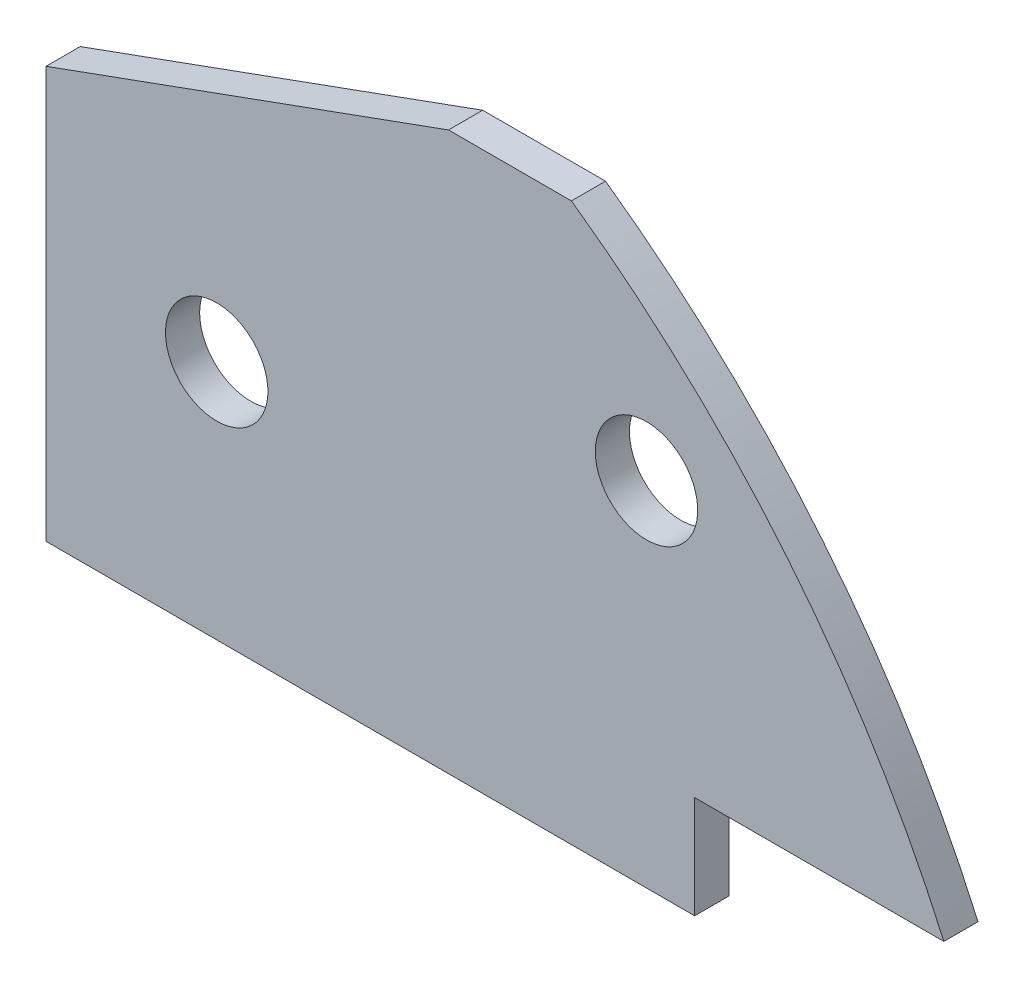
SolidWorks part; units mm, degrees
ref_plane "Front Plane" through (0, 0, 0) normal (0, 0, 1) x (1, 0, 0)
ref_plane "Top Plane" through (0, 0, 0) normal (0, 1, 0) x (1, 0, 0)
ref_plane "Right Plane" through (0, 0, 0) normal (1, 0, 0) x (0, 0, -1)
sketch "Sketch1" plane through (0, 0, 0) normal (0, 0, 1) x (1, 0, 0)
  line L2 (11, 25.5) -> (-11, 25.5)
  line L3 (-11, 25.5) -> (-22.79, 29.7803)
  line L4 (11, 25.5) -> (22.79, 29.7803)
  arc A0 (-22.79, 29.7803) -> (22.79, 29.7803) centre (0, 0) ccw
  arc A1 (-22.79, 29.7803) -> (22.79, 29.7803) centre (0, 0) ccw
  dimension "D2" = 37.5
extrude "Boss-Extrude1" add sketch "Sketch1" along normal blind 3 contours L3 A0 L4 L2
sketch "Sketch2" plane through (0, 0, 3) normal (0, 0, 1) x (1, 0, 0)
  line L0 (0, 0) -> (-25.8, 0) construction
  line L2 (0, 0) -> (0, 15.281) construction
  circle A4 centre (-25.4, 10.4969) radius 1.5
  circle A5 centre (-25.4, -10.4931) radius 1.5
  circle A6 centre (25.4, -10.4931) radius 1.5
  circle A7 centre (25.4, 10.4969) radius 1.5
  point P6 (-25.8, 0)
  dimension "D1" = 25.8
  dimension "D2" = 20.99
extrude "Cut-Extrude3" cut sketch "Sketch2" against normal blind 3
sketch "Sketch3" plane through (0, 0, 3) normal (0, 0, 1) x (1, 0, 0)
  line L1 (-30.76, 21.4493) -> (-30.76, -21.4493)
  line L3 (30.76, 21.4493) -> (30.76, -21.4493)
  arc A0 (-22.79, 29.7803) -> (22.79, 29.7803) centre (0, 0) ccw construction
  arc A1 (-30.76, 21.4493) -> (-30.76, -21.4493) centre (0, 0) ccw
  arc A2 (30.76, 21.4493) -> (30.76, -21.4493) centre (0, 0) cw
  point P10 (-30.76, 0)
extrude "Cut-Extrude4" cut sketch "Sketch3" against normal blind 10
sketch "Sketch4" plane through (0, 0, 3) normal (0, 0, 1) x (1, 0, 0)
  line L0 (-30.76, 21.4493) -> (-30.76, 16.4493) construction
  line L1 (-30.76, -21.4493) -> (-30.76, 21.4493) construction
  line L2 (30.76, 21.4493) -> (30.76, 16.4493) construction
  line L3 (30.76, 21.4493) -> (30.76, -21.4493) construction
  line L4 (-30.76, -21.4493) -> (-30.76, -16.4493) construction
  line L5 (30.76, -21.4493) -> (30.76, -16.4493) construction
  line L6 (-30.76, -16.4493) -> (-33.6997, -16.4493)
  line L7 (-30.76, 16.4493) -> (-33.6997, 16.4493)
  line L8 (30.76, 16.4493) -> (33.6997, 16.4493)
  line L9 (30.76, -16.4493) -> (33.6997, -16.4493)
  line L10 (30.76, -21.4493) -> (30.76, -16.4493)
  line L11 (30.76, 21.4493) -> (30.76, 16.4493)
  line L12 (-30.76, 16.4493) -> (-30.76, 21.4493)
  line L13 (-30.76, -21.4493) -> (-30.76, -16.4493)
  arc A0 (-33.6997, -16.4493) -> (33.6997, -16.4493) centre (0, 0) ccw
  arc A1 (-30.76, 21.4493) -> (-33.6997, 16.4493) centre (0, 0) ccw
  arc A2 (33.6997, 16.4493) -> (30.76, 21.4493) centre (0, 0) ccw
  line M2 (30.76, -21.4493) -> (30.76, 21.4493)
  line M8 (-30.76, 21.4493) -> (-30.76, -21.4493)
  dimension "D1" = 5
  dimension "D2" = 5
extrude "Boss-Extrude2" add sketch "Sketch4" against normal blind 3 contours L6 A0 M8 | A1 L7 M8 | L8 A2 M2 | A0 L9 M2
sketch "Sketch5" plane through (0, 0, 3) normal (0, 0, 1) x (1, 0, 0)
  line L0 (-30.76, 16.4493) -> (-30.2, 16.4493) construction
  line L1 (-30.76, -16.4493) -> (-30.2, -16.4493) construction
  line L2 (0, 0) -> (0, -3.3934) construction
  line L3 (-30.2, -16.4493) -> (-30.76, -16.4493)
  line L4 (-30.2, -16.4493) -> (-30.2, 16.4493)
  line L5 (-30.2, 16.4493) -> (-30.76, 16.4493)
  line L6 (-30.76, -16.4493) -> (-30.76, 16.4493)
  line L7 (30.76, -16.4493) -> (30.2, -16.4493) construction
  line L8 (30.76, 16.4493) -> (30.2, 16.4493) construction
  line L9 (30.76, -16.4493) -> (30.76, 16.4493)
  line L10 (30.2, 16.4493) -> (30.76, 16.4493)
  line L11 (30.2, -16.4493) -> (30.2, 16.4493)
  line L12 (30.2, -16.4493) -> (30.76, -16.4493)
  dimension "D2" = 0.56
extrude "Cut-Extrude5" cut sketch "Sketch5" against normal blind 3
sketch "Sketch6" plane through (0, 0, 3) normal (0, 0, 1) x (1, 0, 0)
  line L1 (-30.2, 16.4493) -> (-30, 16.4493)
  line L2 (-30.2, 16.4493) -> (-30.2, -16.4493)
  line L3 (-30.2, -16.4493) -> (-30, -16.4493)
  line L4 (-30, 16.4493) -> (-30, -16.4493)
  line L5 (30, 16.4493) -> (30, -16.4493)
  line L6 (30.2, -16.4493) -> (30, -16.4493)
  line L7 (30.2, 16.4493) -> (30.2, -16.4493)
  line L8 (30.2, 16.4493) -> (30, 16.4493)
  dimension "D1" = 0.2
extrude "Cut-Extrude6" cut sketch "Sketch6" against normal blind 3
sketch "Sketch7" plane through (0, 0, 3) normal (0, 0, 1) x (1, 0, 0)
  line L0 (0, -37.5) -> (0, -5.6) construction
  line L1 (0, -21.55) -> (-21.15, -21.55) construction
  line L2 (-21.15, -21.55) -> (-19.15, -21.55) construction
  arc A0 (-33.6997, -16.4493) -> (33.6997, -16.4493) centre (0, 0) ccw construction
  circle A1 centre (-19.15, -21.55) radius 2
  circle A2 centre (19.15, -21.55) radius 2
  dimension "D1" = 31.9
  dimension "D2" = 21.15
  dimension "D3" = 2
extrude "Cut-Extrude8" cut sketch "Sketch7" against normal blind 3 contours A1 | A2
sketch "Sketch8" plane through (0, 0, 3) normal (0, 0, 1) x (1, 0, 0)
  line L2 (-33.6997, 16.4493) -> (-37.2997, 16.4493)
  line L3 (33.6997, 16.4493) -> (37.2997, 16.4493)
  line L4 (-22.79, 29.7803) -> (-26.39, 29.7803)
  line L5 (22.79, 29.7803) -> (26.39, 29.7803)
  line L6 (0, 0) -> (0, 7.7073) construction
  arc A0 (-37.2997, 16.4493) -> (-26.39, 29.7803) centre (-7.6125, 3.2837) cw
  arc A1 (37.2997, 16.4493) -> (26.39, 29.7803) centre (7.6125, 3.2837) ccw
  arc A7 (-33.6997, 16.4493) -> (-22.79, 29.7803) centre (0, 0) cw
  arc A8 (22.79, 29.7803) -> (33.6997, 16.4493) centre (0, 0) cw
  dimension "D4" = 3.6
extrude "Boss-Extrude3" add sketch "Sketch8" against normal blind 3
sketch "Sketch9" plane through (0, 0, 3) normal (0, 0, 1) x (1, 0, 0)
  line L0 (0, 0) -> (0, 9.4958) construction
  line L1 (0, -37.5) -> (0, -37.2) construction
  line L2 (4.7339, -37.2) -> (-4.7339, -37.2)
  arc A0 (-33.6997, -16.4493) -> (33.6997, -16.4493) centre (0, 0) ccw construction
  arc A1 (-4.7339, -37.2) -> (4.7339, -37.2) centre (0, 0) ccw
  point P15 (0, -37.2)
  dimension "D1" = 0.3
extrude "Cut-Extrude9" cut sketch "Sketch9" against normal blind 3
sketch "Sketch10" plane through (0, 0, 3) normal (0, 0, 1) x (1, 0, 0)
  line L0 (-33.6997, -16.4493) -> (-37.2997, -16.4493)
  line L1 (-33.6997, -16.4493) -> (-37.2997, -16.4493) construction
  line L2 (0, 0) -> (0, 6.5031) construction
  line L3 (33.6997, -16.4493) -> (37.2997, -16.4493)
  line L4 (-4.7339, -37.2) -> (4.7339, -37.2)
  arc A0 (-37.2997, -16.4493) -> (37.2997, -16.4493) centre (0, 6.1588) ccw
  arc A1 (-33.6997, -16.4493) -> (-4.7339, -37.2) centre (0, 0) ccw
  arc A2 (33.6997, -16.4493) -> (4.7339, -37.2) centre (0, 0) cw
extrude "Boss-Extrude5" add sketch "Sketch10" against normal blind 3
sketch "Sketch11" plane through (0, 0, 3) normal (0, 0, 1) x (1, 0, 0)
  line L0 (-30, 16.4493) -> (-30, 13.4493)
  line L1 (-30, -16.4493) -> (-30, 16.4493) construction
  line L2 (-30, 13.4493) -> (30, 13.4493)
  line L3 (30, 16.4493) -> (30, -16.4493) construction
  line L4 (30, 13.4493) -> (30, 16.4493)
  line L5 (30, 16.4493) -> (37.2997, 16.4493)
  line L6 (-30, 16.4493) -> (-37.2997, 16.4493)
  line L7 (-26.39, 29.7803) -> (-22.79, 29.7803)
  line L8 (-22.79, 29.7803) -> (-11, 25.5)
  line L9 (-11, 25.5) -> (11, 25.5)
  line L10 (11, 25.5) -> (22.79, 29.7803)
  line L11 (22.79, 29.7803) -> (26.39, 29.7803)
  arc A0 (-37.2997, 16.4493) -> (-26.39, 29.7803) centre (-7.6125, 3.2837) cw
  arc A1 (37.2997, 16.4493) -> (26.39, 29.7803) centre (7.6125, 3.2837) ccw
  dimension "D1" = 3
extrude "Cut-Extrude10" cut sketch "Sketch11" against normal blind 2
sketch "Sketch12" plane through (0, 0, 3) normal (0, 0, 1) x (1, 0, 0)
  line L0 (-30, 13.4493) -> (-30, -16.4493)
  line L1 (-30, -16.4493) -> (-37.2997, -16.4493)
  line L2 (-30, 13.4493) -> (30, 13.4493)
  line L3 (30, 13.4493) -> (30, -16.4493)
  line L4 (30, -16.4493) -> (37.2997, -16.4493)
  arc A0 (-37.2997, -16.4493) -> (37.2997, -16.4493) centre (0, 6.1588) ccw
extrude "Cut-Extrude11" cut sketch "Sketch12" against normal blind 3
sketch "Sketch13" plane through (0, 0, 1) normal (0, 0, 1) x (1, 0, 0)
  line L0 (-24.59, 29.7803) -> (-24.59, 23.7803) construction
  line L1 (-22.79, 29.7803) -> (-26.39, 29.7803) construction
  line L2 (-24.59, 23.7803) -> (-28.59, 23.7803) construction
  circle A0 centre (-28.59, 23.7803) radius 1.5
  circle A1 centre (28.59, 23.7803) radius 1.5
  dimension "D3" = 3
  dimension "D1" = 6
  dimension "D2" = 4
extrude "Cut-Extrude12" cut sketch "Sketch13" against normal blind 1
sketch "Sketch14" plane through (0, 0, 0) normal (0, 0, -1) x (-1, 0, 0)
  line L0 (-11, 25.5) -> (11, 25.5)
  line L1 (11, 25.5) -> (22.79, 29.7803)
  line L2 (22.79, 29.7803) -> (26.39, 29.7803)
  line L3 (26.39, 29.7803) -> (41.7917, 29.7803)
  line L4 (41.7917, 29.7803) -> (41.7917, 13.4493)
  line L5 (41.7917, 13.4493) -> (-11, 13.4493)
  line L6 (-30, 13.4493) -> (30, 13.4493) construction
  line L7 (-11, 13.4493) -> (-11, 25.5)
extrude "Cut-Extrude13" cut sketch "Sketch14" against normal blind 10
sketch "Sketch15" plane through (0, 0, 0) normal (0, 0, -1) x (-1, 0, 0)
  line L0 (-11, 25.5) -> (-16, 25.5) construction
  line L1 (-16, 25.5) -> (-16, 20.5) construction
  circle A0 centre (-16, 20.5) radius 1.5
  dimension "D1" = 5
  dimension "D2" = 5
extrude "Cut-Extrude14" cut sketch "Sketch15" against normal blind 10
